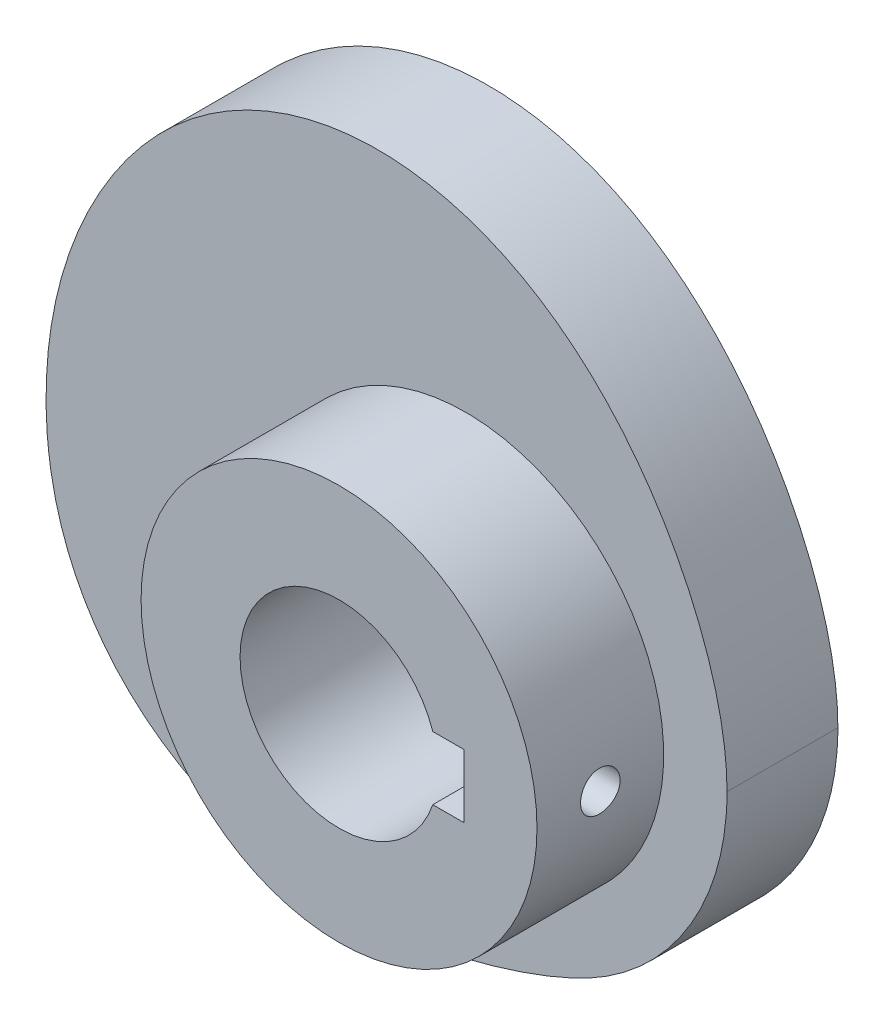
SolidWorks part; units mm, degrees
ref_plane "前视基准面" through (0, 0, 0) normal (0, 0, 1) x (1, 0, 0)
ref_plane "上视基准面" through (0, 0, 0) normal (0, 1, 0) x (1, 0, 0)
ref_plane "右视基准面" through (0, 0, 0) normal (1, 0, 0) x (0, 0, -1)
sketch "草图1" plane through (0, 0, 0) normal (0, 0, 1) x (1, 0, 0)
  spline S0 degree 3 poles (33, 0) (32.9922, 0.5447) (32.9765, 1.6434) (32.8531, 3.3017) (32.6589, 4.9809) (32.3882, 6.6775) (32.0449, 8.3886) (31.6306, 10.1112) (31.1472, 11.8424) (30.5966, 13.5797) (29.9803, 15.3203) (29.2998, 17.0616) (28.5559, 18.8008) (27.7492, 20.535) (26.8798, 22.2611) (25.9473, 23.976) (24.951, 25.6761) (23.8898, 27.3577) (22.7622, 29.0167) (21.5666, 30.6486) (20.3011, 32.2485) (18.9641, 33.8111) (17.554, 35.3308) (16.0693, 36.8012) (14.5093, 38.2157) (12.8735, 39.5674) (11.1622, 40.8489) (9.3764, 42.0526) (7.518, 43.1707) (5.5895, 44.1955) (3.5945, 45.1193) (1.5373, 45.9346) (-0.5767, 46.6343) (-2.7416, 47.2115) (-4.9506, 47.6602) (-7.1962, 47.9748) (-9.4704, 48.1506) (-11.7647, 48.1836) (-14.0703, 48.0706) (-16.378, 47.8095) (-18.6785, 47.399) (-20.9626, 46.8387) (-23.2211, 46.1292) (-25.4448, 45.2719) (-27.6251, 44.2692) (-29.7535, 43.1241) (-31.8222, 41.8408) (-33.8238, 40.4236) (-35.7515, 38.878) (-37.5995, 37.2096) (-39.3622, 35.4247) (-41.0352, 33.5297) (-42.6148, 31.5313) (-44.0978, 29.4365) (-45.4811, 27.2531) (-46.7607, 24.9937) (-47.9307, 22.6695) (-48.9853, 20.2904) (-49.9219, 17.8623) (-50.7382, 15.3913) (-51.4323, 12.8831) (-52.0025, 10.3439) (-52.4474, 7.7798) (-52.766, 5.197) (-52.9573, 2.6016) (-53.0216, 0.0092) (-52.9568, -2.5568) (-52.7688, -5.0771) (-52.5221, -6.7266) (-52.3999, -7.5441) knots 0 0 0 0 0.010896 0.021979 0.03325 0.044705 0.056341 0.068155 0.080141 0.092294 0.104608 0.117075 0.12969 0.142444 0.155333 0.16835 0.18149 0.194748 0.208123 0.221611 0.235212 0.248923 0.262744 0.276675 0.290714 0.30486 0.319112 0.333468 0.347926 0.362483 0.377137 0.391887 0.406728 0.421661 0.436684 0.451796 0.466997 0.482288 0.49767 0.513146 0.528718 0.54439 0.560164 0.576046 0.592037 0.608143 0.624366 0.64071 0.657177 0.67377 0.69049 0.707338 0.724316 0.741425 0.758663 0.776004 0.793351 0.810699 0.828047 0.845394 0.862742 0.88009 0.897437 0.914785 0.932132 0.94948 0.966643 0.983468 1 1 1 1
  spline S1 degree 3 poles (-52.3999, -7.5441) (-52.2514, -8.3444) (-51.9565, -9.9343) (-51.4314, -11.8813) (-50.9466, -13.4024) (-50.5478, -14.5208) (-50.114, -15.6197) (-49.6452, -16.6982) (-49.142, -17.7553) (-48.6047, -18.7903) (-48.034, -19.8023) (-47.4304, -20.7905) (-46.7947, -21.754) (-46.1277, -22.6919) (-45.4301, -23.6035) (-44.4617, -24.7814) (-43.1792, -26.185) (-41.5326, -27.7539) (-39.7889, -29.2011) (-37.9583, -30.5229) (-36.0509, -31.7166) (-34.0776, -32.7807) (-32.0488, -33.7149) (-29.9754, -34.52) (-27.8673, -35.1982) (-25.7344, -35.7527) (-23.5857, -36.1876) (-21.4291, -36.5081) (-19.2718, -36.7203) (-17.1198, -36.8306) (-14.9782, -36.846) (-12.8509, -36.7737) (-10.7409, -36.6209) (-8.6506, -36.395) (-6.5817, -36.1029) (-4.5356, -35.751) (-2.5139, -35.3456) (-0.5183, -34.8919) (1.4488, -34.3946) (3.3841, -33.8575) (5.2834, -33.2836) (7.1412, -32.6749) (8.9507, -32.0326) (10.7039, -31.3571) (12.3913, -30.6488) (14.002, -29.9079) (15.5253, -29.135) (16.9672, -28.3198) (18.3412, -27.4495) (19.666, -26.5165) (20.9434, -25.5196) (22.1703, -24.4612) (23.3439, -23.3439) (24.4612, -22.1703) (25.5196, -20.9434) (26.5165, -19.666) (27.4495, -18.3412) (28.3164, -16.9722) (29.1151, -15.5623) (29.8436, -14.115) (30.5003, -12.6336) (31.0834, -11.1218) (31.5917, -9.5832) (32.0239, -8.0216) (32.3788, -6.4406) (32.6562, -4.8441) (32.8533, -3.2359) (32.977, -1.6199) (32.9923, -0.54) (33, 0) knots 0 0 0 0 0.020431 0.040588 0.050577 0.060512 0.070397 0.080235 0.090031 0.099788 0.10951 0.119198 0.128856 0.138486 0.148091 0.157672 0.176767 0.195786 0.214735 0.233619 0.252438 0.271191 0.289874 0.308482 0.327007 0.345444 0.363786 0.382028 0.400165 0.418194 0.436113 0.453923 0.471624 0.489218 0.506703 0.524079 0.541338 0.558471 0.575459 0.592278 0.608896 0.625272 0.64136 0.657103 0.67244 0.687302 0.70161 0.715318 0.728874 0.74243 0.755987 0.769543 0.783099 0.796656 0.810212 0.823768 0.837324 0.850881 0.864437 0.877993 0.89155 0.905106 0.918662 0.932219 0.945775 0.959331 0.972887 0.986444 1 1 1 1
extrude "凸台-拉伸1" add sketch "草图1" along normal blind 14
sketch "草图2" plane through (0, 0, 0) normal (0, 0, 1) x (1, 0, 0)
  circle A0 centre (0, 0) radius 25
extrude "凸台-拉伸2" add sketch "草图2" along normal blind 30
ref_plane "基准面1" through (0, 0, 30) normal (0, 0, 1) x (1, 0, 0)
sketch "草图3" plane through (0, 0, 30) normal (0, 0, 1) x (1, 0, 0)
  circle A0 centre (0, 0) radius 12.5
extrude "切除-拉伸1" cut sketch "草图3" against normal through all
sketch3d "3D草图1"
  line L0 (0, 0, 22) -> (27, 0, 22)
sweep "切除-扫描2" cut path "3D草图1" circular profile diameter 5 parameters "D3"=5
sketch "草图8" plane through (0, 0, 0) normal (0, 0, 1) x (1, 0, 0)
  line L0 (0, -4) -> (15.8, -4)
  line L1 (15.8, -4) -> (15.8, 4)
  line L2 (15.8, 4) -> (0, 4)
  line L3 (0, 4) -> (0, -4)
extrude "切除-拉伸3" cut sketch "草图8" along normal through all
